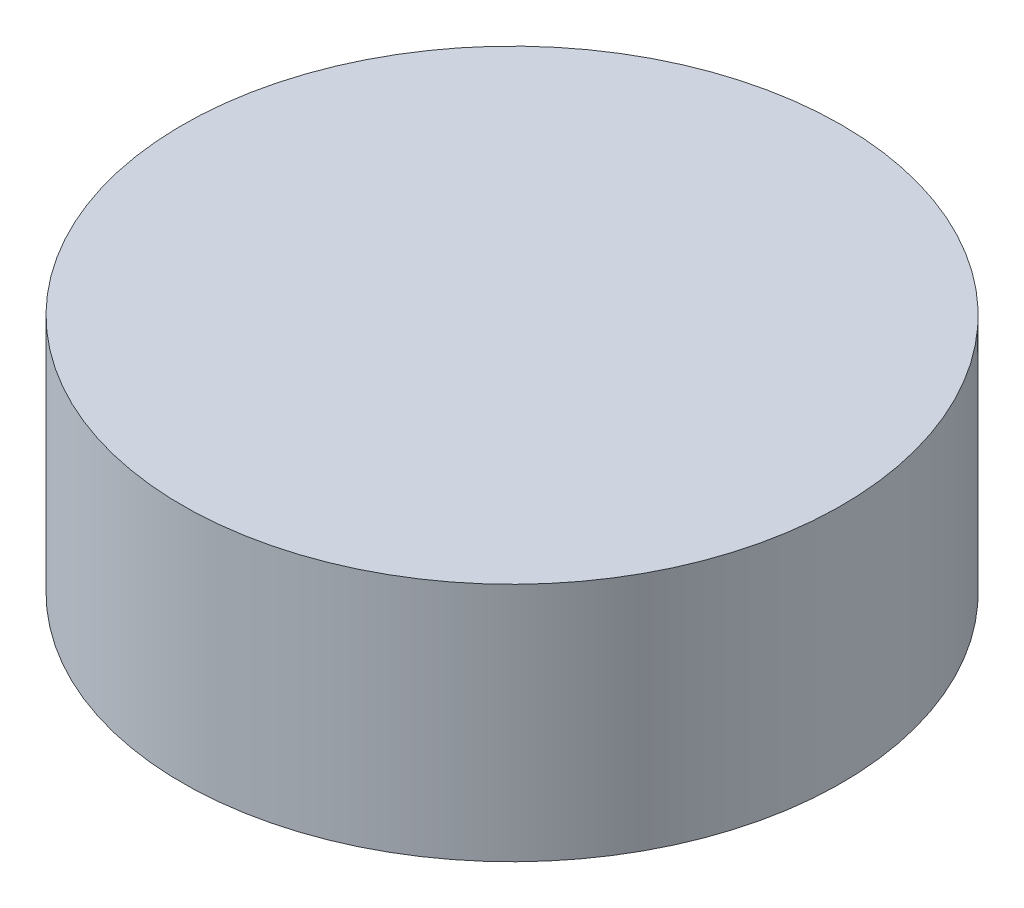
SolidWorks part; units mm, degrees
material "ПК/АБС"
ref_plane "Спереди" through (0, 0, 0) normal (0, 0, 1) x (1, 0, 0)
ref_plane "Сверху" through (0, 0, 0) normal (0, 1, 0) x (1, 0, 0)
ref_plane "Справа" through (0, 0, 0) normal (1, 0, 0) x (0, 0, -1)
sketch "Эскиз2" plane through (0, 0, 0) normal (0, 0, 1) x (1, 0, 0)
  line L0 (0, 0) -> (0, 74.988) construction
  line L1 (0, 0) -> (-48, 0)
  line L2 (-48, 0) -> (-48, -35)
  line L3 (-48, -35) -> (-46, -35)
  line L4 (-46, -35) -> (-46, -5.5)
  line L5 (-43, -2.5) -> (0, -2.5)
  line L6 (0, -2.5) -> (0, 0)
  arc A0 (-46, -5.5) -> (-43, -2.5) centre (-43, -5.5) cw
  circle A1 centre (0, 17.2934) radius 30 construction
  point P13 (0, 17.2934)
  dimension "D5" = 3
  dimension "D6" = 60
  dimension "D1" = 48
  dimension "D2" = 35
  dimension "D3" = 2
  dimension "D4" = 2.5
revolve "Основа" add sketch "Эскиз2" angle 360 about L0
sketch "Эскиз4" [suppressed] plane through (0, 0, 0) normal (0, 0, 1) x (1, 0, 0)
  line L0 (0, 0) -> (0, -18) construction
  line L1 (-5, -29) -> (5, -29) construction
  line L2 (-5, -29) -> (-5, -7) construction
  line L3 (-5, -7) -> (5, -7)
  line L4 (5, -29) -> (5, -7) construction
  line L5 (-5, -29) -> (5, -7) construction
  line L6 (-5, -7) -> (5, -29) construction
  line L7 (2.5, 0) -> (-2.5, 0) construction
  line L8 (-5, -7) -> (0, -29)
  line L9 (0, -29) -> (5, -7)
  line L10 (-48, -35) -> (48, -35) construction
  point P0 (0, -18)
  point P12 (0, 0)
  dimension "D1" = 22
  dimension "D2" = 10
  dimension "D3" = 7
  dimension "D4" = 25.609
  dimension "D5" = 6
  dimension "D6" = 77.196
extrude "Вырез облегчение" [suppressed] cut sketch "Эскиз4" against normal mid plane 120
pattern_circular "Круговой массив1" [suppressed] count 5 over 360
